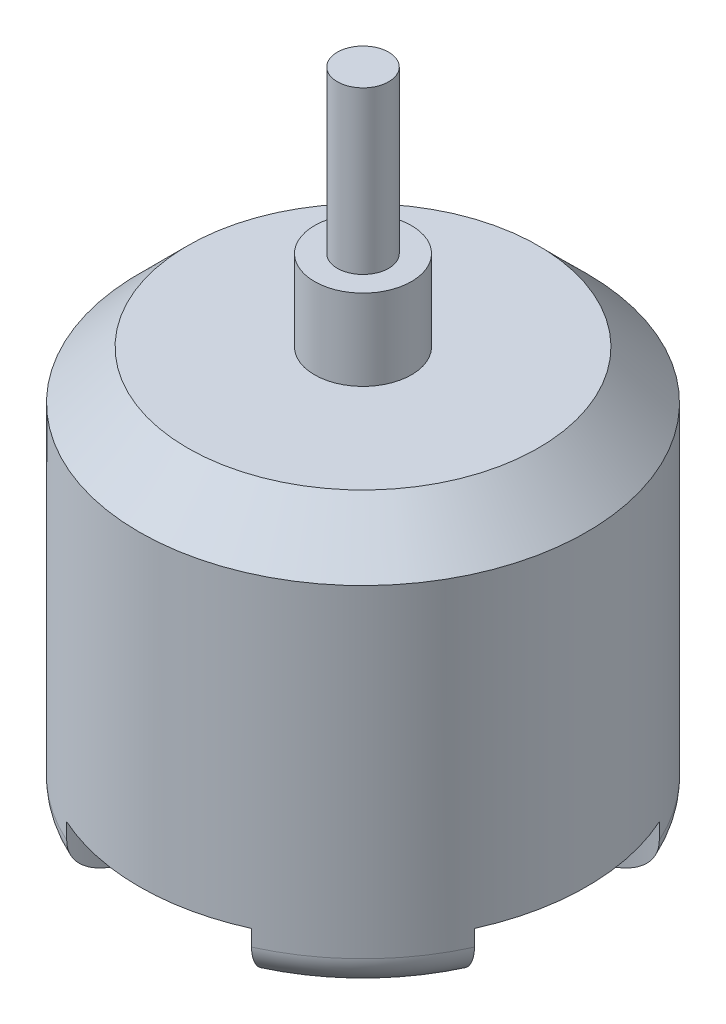
SolidWorks part; units mm, degrees
ref_plane "정면" through (0, 0, 0) normal (0, 0, 1) x (1, 0, 0)
ref_plane "윗면" through (0, 0, 0) normal (0, 1, 0) x (1, 0, 0)
ref_plane "우측면" through (0, 0, 0) normal (1, 0, 0) x (0, 0, -1)
sketch "스케치1" plane through (0, 0, 0) normal (0, 0, 1) x (1, 0, 0)
  line L0 (0, 0) -> (0, -6.0117) construction
  line L1 (0, 0) -> (13.85, 0)
  line L3 (13.85, 0) -> (13.85, 19)
  line L5 (3, 22) -> (10.85, 22)
  line L6 (1.5875, 27) -> (1.5875, 37)
  line L7 (1.5875, 37) -> (0, 37)
  line L8 (0, 37) -> (0, 0)
  line L9 (3, 22) -> (3, 27)
  line L10 (3, 27) -> (1.5875, 27)
  line L11 (13.85, 19) -> (10.85, 22)
  point P2 (0, 0)
  point P8 (0.7937, 37)
  point P9 (0, 0)
  dimension "D1" = 37
  dimension "D2" = 10
  dimension "D3" = 13.85
  dimension "D4" = 22
  dimension "D5" = 3
  dimension "D6" = 3
  dimension "D7" = 3
  dimension "D8" = 1.5875
revolve "회전1" add sketch "스케치1" angle 360 about L0
sketch "스케치2" plane through (0, 0, 0) normal (0, -1, 0) x (1, 0, 0)
  line L0 (0, -18.7821) -> (0, 18.7821) construction
  line L1 (-28.5993, 0) -> (28.5993, 0) construction
  circle A0 centre (0, 0) radius 5 construction
  circle A1 centre (0, 0) radius 8 construction
  circle A2 centre (0, 0) radius 9.5 construction
  circle A4 centre (0, 0) radius 13.85
  arc A5 (-5.7181, 12.6145) -> (5.7181, 12.6145) centre (0, 13.85) ccw
  arc A6 (12.6145, 5.7181) -> (12.6145, -5.7181) centre (13.85, 0) ccw
  arc A7 (5.7181, -12.6145) -> (-5.7181, -12.6145) centre (0, -13.85) ccw
  arc A8 (-12.6145, -5.7181) -> (-12.6145, 5.7181) centre (-13.85, 0) ccw
  point P7 (0, 0)
  point P10 (0, 0)
  point P12 (0, 0)
  point P16 (0, 0)
  point P17 (0, 0)
  point P27 (0, 0)
  point P28 (0, 0)
  dimension "D1" = 10
  dimension "D2" = 16
  dimension "D3" = 19
  dimension "D5" = 27.7
  dimension "D4" = 4
extrude "보스-돌출1" add sketch "스케치2" along normal blind 3 contours A8 A4 A7 A6 A5
fillet "필렛1" radius 2 4 edges at (-9.7934, -3, -9.7934) (9.7934, -3, -9.7934) (9.7934, -3, 9.7934) (-9.7934, -3, 9.7934)
hole_wizard "M3 여유 구멍1" positions "스케치8" profile "스케치9" hole size "M3" standard "ISO"
sketch "스케치8" plane through (0, -3, 0) normal (0, -1, 0) x (-1, 0, 0)
  line L0 (6.7175, 6.7175) -> (-6.7175, -6.7175) construction
  line L2 (0, 0) -> (-17.0832, 0) construction
  line L4 (-5.6569, 5.6569) -> (5.6569, -5.6569) construction
  point P0 (5.6569, -5.6569)
  point P2 (-5.6569, 5.6569)
  point P4 (-6.7175, -6.7175)
  point P6 (6.7175, 6.7175)
  point P13 (0, 0)
  point P26 (0, 0)
  dimension "D1" = 19
  dimension "D2" = 45
  dimension "D3" = 16
sketch "스케치9" plane through (-5.6569, -3, 5.6569) normal (1, 0, 0) x (0, 0, -1)
  line L0 (0, 0) -> (0, 8.0215)
  line L1 (0, 8.0215) -> (1.7, 7)
  line L2 (1.7, 7) -> (1.7, 0)
  line L5 (1.7, 0) -> (0, 0)
  line L10 (0, 8.0215) -> (-1.7, 7) construction
  line L11 (0, -6.35) -> (0, 107.95) construction
  dimension "구멍 지름" = 3.4
  dimension "구멍 깊이" = 7
  dimension "드릴 각도" = 118
sketch "스케치10" plane through (0, -3, 0) normal (0, -1, 0) x (1, 0, 0)
  circle A0 centre (0, 0) radius 5
  dimension "D1" = 10
extrude "보스-돌출2" add sketch "스케치10" along normal blind 1
